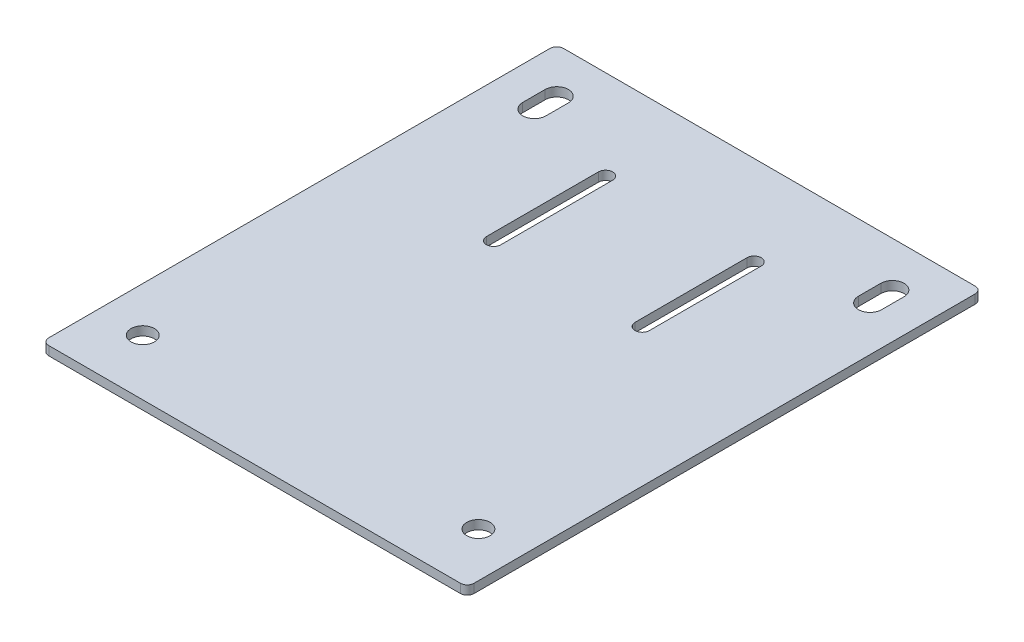
SolidWorks part; units mm, degrees
ref_plane "Front Plane" through (0, 0, 0) normal (0, 0, 1) x (1, 0, 0)
ref_plane "Top Plane" through (0, 0, 0) normal (0, 1, 0) x (1, 0, 0)
ref_plane "Right Plane" through (0, 0, 0) normal (1, 0, 0) x (0, 0, -1)
sketch "Sketch1" plane through (0, 0, 0) normal (0, 1, 0) x (1, 0, 0)
  line L0 (-47.5, 45) -> (47.5, 45) construction
  line L1 (-47.5, -57.5) -> (47.5, -57.5)
  line L2 (-47.5, -57.5) -> (-47.5, 57.5)
  line L3 (-47.5, 57.5) -> (47.5, 57.5)
  line L4 (47.5, -57.5) -> (47.5, 57.5)
  line L5 (-47.5, -57.5) -> (47.5, 57.5) construction
  line L6 (-47.5, 57.5) -> (47.5, -57.5) construction
  line L7 (0, 57.5) -> (0, -57.5) construction
  line L8 (-47.5, 0) -> (47.5, 0) construction
  line L9 (-47.5, -45) -> (47.5, -45) construction
  circle A0 centre (-37.5, 45) radius 2.6
  circle A1 centre (37.5, 45) radius 2.6
  circle A2 centre (37.5, -45) radius 2.6
  circle A3 centre (-37.5, -45) radius 2.6
  point P0 (0, 0)
  dimension "D1" = 5.2
  dimension "D2" = 75
  dimension "D3" = 95
  dimension "D4" = 90
  dimension "D5" = 115
extrude "Boss-Extrude1" add sketch "Sketch1" along normal blind 2
sketch "Sketch2" plane through (0, 2, 0) normal (0, 1, 0) x (1, 0, 0)
  line L0 (0, 0) -> (0, 57.5) construction
  line L1 (47.5, 57.5) -> (-47.5, 57.5) construction
  line L2 (-37.5, 45) -> (-37.5, 56.49) construction
  line L3 (-37.5, 47.5) -> (-37.5, 42.5) construction
  line L4 (-34.9, 47.5) -> (-34.9, 42.5)
  line L5 (-40.1, 47.5) -> (-40.1, 42.5)
  line L6 (37.5, 47.5) -> (37.5, 42.5) construction
  line L7 (34.9, 47.5) -> (34.9, 42.5)
  line L8 (40.1, 47.5) -> (40.1, 42.5)
  arc A0 (-34.9, 47.5) -> (-40.1, 47.5) centre (-37.5, 47.5) ccw
  arc A1 (-40.1, 42.5) -> (-34.9, 42.5) centre (-37.5, 42.5) ccw
  arc A2 (34.9, 47.5) -> (40.1, 47.5) centre (37.5, 47.5) cw
  arc A3 (40.1, 42.5) -> (34.9, 42.5) centre (37.5, 42.5) cw
  point P10 (-37.5, 45)
  point P17 (37.5, 45)
  dimension "D2" = 2.6
  dimension "D1" = 5
extrude "Cut-Extrude1" cut sketch "Sketch2" against normal through all
fillet "Fillet1" radius 1.5 4 edges at (47.5, 1, 57.5) (-47.5, 1, 57.5) (47.5, 1, -57.5) (-47.5, 1, -57.5)
sketch "Sketch3" plane through (0, 0, 0) normal (0, -1, 0) x (1, 0, 0)
  line L0 (0, -57.5) -> (0, 57.5) construction
  line L1 (46, -57.5) -> (-46, -57.5) construction
  line L2 (-46, 57.5) -> (46, 57.5) construction
  line L3 (16.6, -37.5) -> (16.6, -12.5) construction
  line L4 (15, -37.5) -> (15, -12.5)
  line L5 (18.2, -37.5) -> (18.2, -12.5)
  line L6 (-16.6, -37.5) -> (-16.6, -12.5) construction
  line L7 (-15, -37.5) -> (-15, -12.5)
  line L8 (-18.2, -37.5) -> (-18.2, -12.5)
  arc A0 (15, -37.5) -> (18.2, -37.5) centre (16.6, -37.5) ccw
  arc A1 (18.2, -12.5) -> (15, -12.5) centre (16.6, -12.5) ccw
  arc A2 (-15, -37.5) -> (-18.2, -37.5) centre (-16.6, -37.5) cw
  arc A3 (-18.2, -12.5) -> (-15, -12.5) centre (-16.6, -12.5) cw
  point P8 (16.6, -25)
  point P15 (-16.6, -25)
  dimension "D1" = 1.6
  dimension "D2" = 15
  dimension "D3" = 20
  dimension "D4" = 25
extrude "Cut-Extrude2" cut sketch "Sketch3" against normal through all
